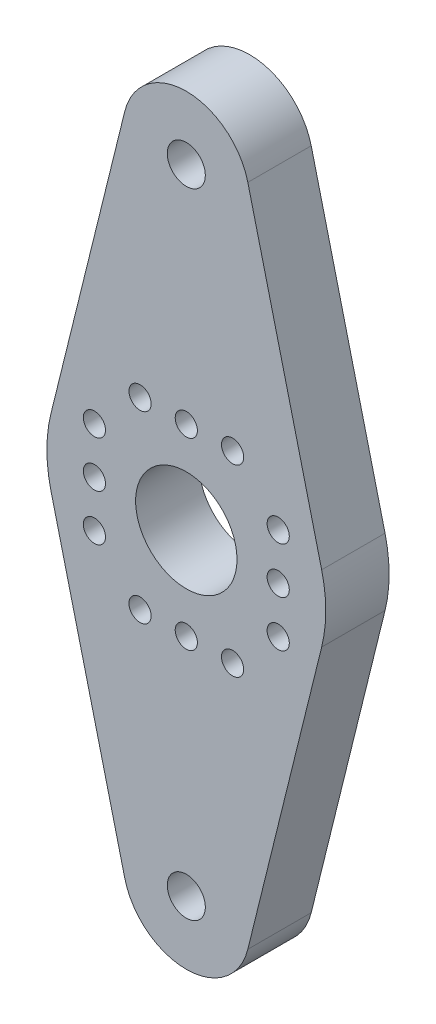
SolidWorks part; units mm, degrees
ref_plane "Plan de face" through (0, 0, 0) normal (0, 0, 1) x (1, 0, 0)
ref_plane "Plan de dessus" through (0, 0, 0) normal (0, 1, 0) x (1, 0, 0)
ref_plane "Plan de droite" through (0, 0, 0) normal (1, 0, 0) x (0, 0, -1)
sketch "Esquisse1" plane through (0, 0, 0) normal (0, 0, 1) x (1, 0, 0)
  line L0 (0, 0) -> (7.25, 0) construction
  line L1 (7.25, 3.65) -> (7.25, 0) construction
  line L2 (0, 0) -> (7.25, 0) construction
  line L3 (0, 0) -> (0, 25) construction
  line L4 (-10.6785, 2.64) -> (-4.8539, 26.2)
  line L5 (4.8539, 26.2) -> (10.6785, 2.64)
  line L6 (0, 0) -> (-11, 0) construction
  line L7 (4.8539, -26.2) -> (10.6785, -2.64)
  line L8 (-10.6785, -2.64) -> (-4.8539, -26.2)
  circle A0 centre (0, 0) radius 10.5 construction
  circle A1 centre (0, 0) radius 4
  circle A2 centre (7.25, 0) radius 0.875
  circle A3 centre (7.25, 3.65) radius 0.875
  circle A4 centre (7.25, -3.65) radius 0.875
  circle A5 centre (3.65, -7.25) radius 0.875
  circle A6 centre (0, -7.25) radius 0.875
  circle A7 centre (-3.65, -7.25) radius 0.875
  circle A8 centre (-7.25, -3.65) radius 0.875
  circle A9 centre (-7.25, 0) radius 0.875
  circle A10 centre (-7.25, 3.65) radius 0.875
  circle A11 centre (-3.65, 7.25) radius 0.875
  circle A12 centre (0, 7.25) radius 0.875
  circle A13 centre (3.65, 7.25) radius 0.875
  circle A14 centre (0, 25) radius 1.5
  arc A15 (-4.8539, 26.2) -> (4.8539, 26.2) centre (0, 25) cw
  arc A16 (-10.6785, -2.64) -> (-10.6785, 2.64) centre (0, 0) cw
  arc A17 (10.6785, -2.64) -> (10.6785, 2.64) centre (0, 0) ccw
  circle A18 centre (0, -25) radius 1.5
  arc A19 (-4.8539, -26.2) -> (4.8539, -26.2) centre (0, -25) ccw
  dimension "D1" = 21
  dimension "D2" = 8
  dimension "D5" = 1.75
  dimension "D8" = 5
  dimension "D9" = 11
  dimension "D10" = 3
  dimension "D3" = 7.25
  dimension "D4" = 3.65
  dimension "D7" = 25
  dimension "D6" = 4
extrude "Boss.-Extru.1" add sketch "Esquisse1" along normal blind 5
